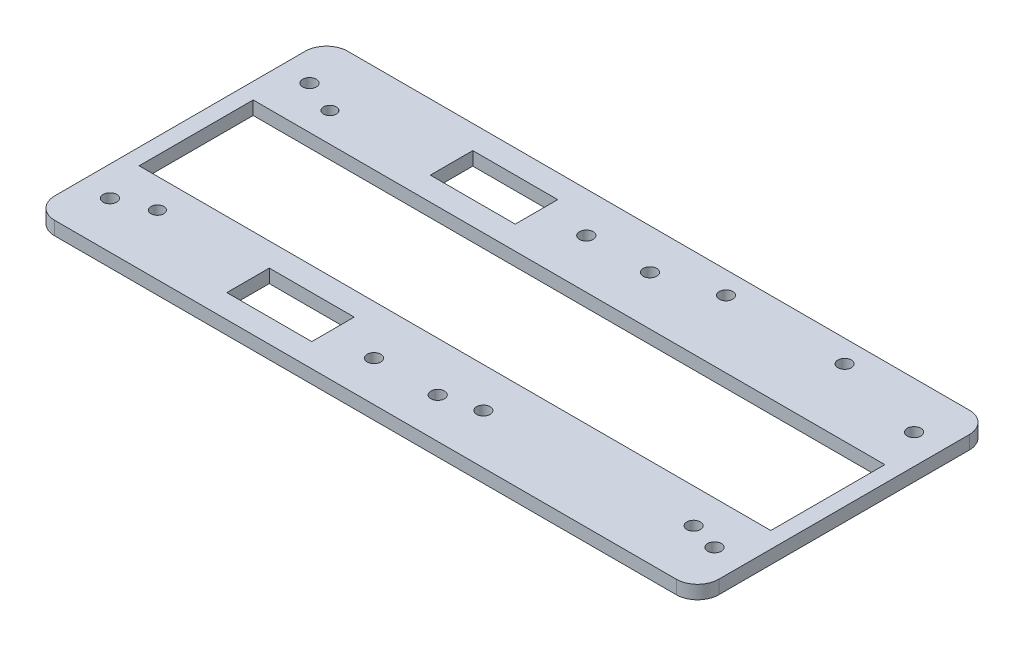
SolidWorks part; units mm, degrees
ref_plane "Front Plane" through (0, 0, 0) normal (0, 0, 1) x (1, 0, 0)
ref_plane "Top Plane" through (0, 0, 0) normal (0, 1, 0) x (1, 0, 0)
ref_plane "Right Plane" through (0, 0, 0) normal (1, 0, 0) x (0, 0, -1)
sketch "Sketch2" plane through (0, 0, 0) normal (0, 1, 0) x (1, 0, 0)
  line L1 (-78.2, 34.5) -> (78.2, 34.5)
  line L2 (-78.2, 34.5) -> (-78.2, -34.5)
  line L3 (-78.2, -34.5) -> (78.2, -34.5)
  line L4 (78.2, 34.5) -> (78.2, -34.5)
  line L5 (-78.2, 34.5) -> (78.2, -34.5) construction
  line L6 (-78.2, -34.5) -> (78.2, 34.5) construction
  point P0 (0, 0)
  dimension "D1" = 69
  dimension "D2" = 156.4
extrude "Boss-Extrude1" add sketch "Sketch2" along normal blind 3.175
ref_plane "Plane1" through (0, 0, 0) normal (0, 0, -1) x (-1, 0, 0)
sketch "Sketch4" plane through (0, 3.175, 0) normal (0, 1, 0) x (1, 0, 0)
  line L0 (78.2, 0) -> (-78.2, 0) construction
  line L1 (78.2, -34.5) -> (71.2, -34.5) construction
  line L2 (78.2, -34.5) -> (78.2, -23.5) construction
  line L3 (78.2, -23.5) -> (71.2, -23.5) construction
  line L4 (71.2, -34.5) -> (71.2, -23.5) construction
  line L5 (78.2, -34.5) -> (71.2, -23.5) construction
  line L6 (78.2, -23.5) -> (71.2, -34.5) construction
  line L7 (78.2, -34.5) -> (78.2, 34.5) construction
  line L8 (-78.2, 34.5) -> (-78.2, -34.5) construction
  line L9 (-78.2, 0) -> (1.1337, 0) construction
  line L10 (1.1337, 0) -> (0, -34.5) construction
  line L11 (-78.2, -34.5) -> (78.2, -34.5) construction
  line L12 (0, -34.5) -> (0, 34.5) construction
  line L13 (78.2, 34.5) -> (-78.2, 34.5) construction
  circle A0 centre (71.2, -23.5) radius 1.6
  circle A1 centre (71.2, 23.5) radius 1.6
  circle A2 centre (-71.2, 23.5) radius 1.6
  circle A3 centre (-71.2, -23.5) radius 1.6
  point P4 (74.7, -29)
  dimension "D3" = 3.2
  dimension "D1" = 7
  dimension "D2" = 11
extrude "Cut-Extrude1" cut sketch "Sketch4" against normal through all
sketch "Sketch6" plane through (0, 0, 0) normal (0, -1, 0) x (1, 0, 0)
  circle A0 centre (49.09, -29.25) radius 1.5875 construction
  circle A1 centre (49.09, -29.25) radius 1.5875
  circle A2 centre (21.15, -29.25) radius 1.5875 construction
  circle A3 centre (21.15, -29.25) radius 1.5875
  circle A4 centre (64.33, 21.55) radius 1.5875 construction
  circle A5 centre (64.33, 21.55) radius 1.5875
  circle A6 centre (16.07, 22.82) radius 1.5875 construction
  circle A7 centre (16.07, 22.82) radius 1.5875
extrude "Cut-Extrude2" cut sketch "Sketch6" against normal through all
sketch "Sketch7" plane through (0, 0, 0) normal (0, -1, 0) x (-1, 0, 0)
  line L0 (63.2, 34.5) -> (63.2, -34.5) construction
  line L1 (-78.2, 34.5) -> (78.2, 34.5) construction
  line L2 (78.2, -34.5) -> (-78.2, -34.5) construction
  line L3 (78.2, 34.5) -> (78.2, -34.5) construction
  line L4 (63.2, 0) -> (78.2, 0) construction
  circle A0 centre (63.2, -20.32) radius 1.5
  circle A1 centre (63.2, 20.32) radius 1.5
  point P6 (78.2, 0)
  dimension "D3" = 3
  dimension "D1" = 15
  dimension "D2" = 20.32
extrude "Cut-Extrude3" cut sketch "Sketch7" against normal through all
sketch "Sketch8" plane through (0, 0, 0) normal (0, -1, 0) x (1, 0, 0)
  line L0 (-72.39, 11.43) -> (-72.39, -11.43) construction
  line L1 (-72.39, 11.43) -> (72.39, 11.43) construction
  line L2 (-72.39, -11.43) -> (72.39, -11.43) construction
  line L3 (72.39, 11.43) -> (72.39, -11.43) construction
  line L4 (-72.39, 11.43) -> (-72.39, -11.43) construction
  line L5 (-72.39, 11.43) -> (72.39, 11.43) construction
  line L6 (-72.39, -11.43) -> (72.39, -11.43) construction
  line L7 (72.39, 11.43) -> (72.39, -11.43) construction
  line L8 (-73.39, 12.43) -> (73.39, 12.43)
  line L9 (73.39, 12.43) -> (73.39, -12.43)
  line L10 (-73.39, -12.43) -> (73.39, -12.43)
  line L11 (-73.39, 12.43) -> (-73.39, -12.43)
  dimension "D1" = 1
extrude "Cut-Extrude4" cut sketch "Sketch8" against normal through all
sketch "Sketch10" plane through (0, 3.175, 0) normal (0, 1, 0) x (1, 0, 0)
  line L1 (-7.5, 25) -> (7.5, 25) construction
  line L2 (-7.5, 25) -> (-7.5, -25) construction
  line L3 (-7.5, -25) -> (7.5, -25) construction
  line L4 (7.5, 25) -> (7.5, -25) construction
  line L5 (-7.5, 25) -> (7.5, -25) construction
  line L6 (-7.5, -25) -> (7.5, 25) construction
  circle A0 centre (-7.5, -25) radius 1.6
  circle A1 centre (7.5, -25) radius 1.6
  circle A2 centre (7.5, 25) radius 1.6
  circle A3 centre (-7.5, 25) radius 1.6
  point P0 (0, 0)
  dimension "D3" = 3.2
  dimension "D1" = 15
  dimension "D2" = 50
extrude "Cut-Extrude6" cut sketch "Sketch10" against normal through all
sketch "Sketch11" plane through (0, 0, 0) normal (0, -1, 0) x (1, 0, 0)
  line L0 (74.39, 13.43) -> (-74.39, 13.43) construction
  line L1 (-74.39, 13.43) -> (-74.39, -13.43) construction
  line L2 (-74.39, -13.43) -> (74.39, -13.43) construction
  line L3 (74.39, -13.43) -> (74.39, 13.43) construction
  line L4 (74.39, 13.43) -> (-74.39, 13.43)
  line L5 (-74.39, 13.43) -> (-74.39, -13.43)
  line L6 (-74.39, -13.43) -> (74.39, -13.43)
  line L7 (74.39, -13.43) -> (74.39, 13.43)
extrude "Cut-Extrude7" cut sketch "Sketch11" against normal through all
sketch "Sketch12" plane through (0, 0, 0) normal (0, -1, 0) x (1, 0, 0)
  line L0 (-28.2, -34.5) -> (-28.2, -13.43) construction
  line L1 (78.2, -34.5) -> (-78.2, -34.5) construction
  line L2 (-74.39, -13.43) -> (74.39, -13.43) construction
  line L3 (-78.2, -34.5) -> (-78.2, 34.5) construction
  line L4 (-78.2, 0) -> (78.2, 0) construction
  line L5 (-38.2, -18.965) -> (-18.2, -18.965)
  line L6 (-38.2, -18.965) -> (-38.2, -28.965)
  line L7 (-38.2, -28.965) -> (-18.2, -28.965)
  line L8 (-18.2, -18.965) -> (-18.2, -28.965)
  line L9 (-38.2, -18.965) -> (-18.2, -28.965) construction
  line L10 (-38.2, -28.965) -> (-18.2, -18.965) construction
  line L11 (78.2, 34.5) -> (78.2, -34.5) construction
  line L12 (-18.2, 18.965) -> (-18.2, 28.965)
  line L13 (-38.2, 18.965) -> (-18.2, 18.965)
  line L14 (-38.2, 18.965) -> (-38.2, 28.965)
  line L15 (-38.2, 28.965) -> (-18.2, 28.965)
  point P8 (-28.2, -23.965)
  dimension "D1" = 50
  dimension "D2" = 10
  dimension "D3" = 20
extrude "Cut-Extrude8" cut sketch "Sketch12" against normal through all
fillet "Fillet1" radius 5 4 edges at (78.2, 1.5875, -34.5) (78.2, 1.5875, 34.5) (-78.2, 1.5875, -34.5) (-78.2, 1.5875, 34.5)
